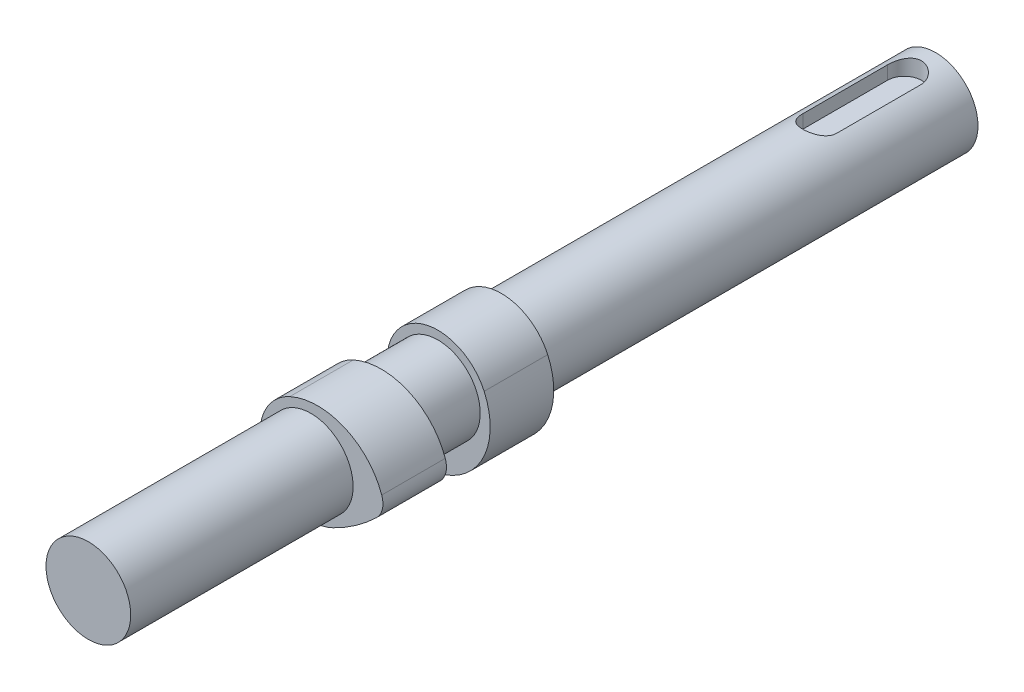
SolidWorks part; units mm, degrees
ref_plane "Front Plane" through (0, 0, 0) normal (0, 0, 1) x (1, 0, 0)
ref_plane "Top Plane" through (0, 0, 0) normal (0, 1, 0) x (1, 0, 0)
ref_plane "Right Plane" through (0, 0, 0) normal (1, 0, 0) x (0, 0, -1)
sketch "Sketch1" plane through (0, 0, 0) normal (0, 0, 1) x (1, 0, 0)
  circle A0 centre (0, 0) radius 10
  dimension "D1" = 20
extrude "Boss-Extrude1" add sketch "Sketch1" along normal blind 200
ref_plane "Plane1" through (0, 6, 0) normal (0, 1, 0) x (1, 0, 0)
sketch "Sketch2" plane through (0, 6, 0) normal (0, 1, 0) x (1, 0, 0)
  line L0 (0, -7.3661) -> (0, -27.3661) construction
  line L1 (4, -7.3661) -> (4, -27.3661)
  line L2 (-4, -7.3661) -> (-4, -27.3661)
  arc A0 (4, -7.3661) -> (-4, -7.3661) centre (0, -7.3661) ccw
  arc A1 (-4, -27.3661) -> (4, -27.3661) centre (0, -27.3661) ccw
  point P3 (0, -17.3661)
  point P8 (0, -3.3661)
  point P9 (0, -31.3661)
  point P10 (0, -7.3661)
  dimension "D3" = 4
  dimension "D1" = 28
  dimension "D2" = 20
extrude "Cut-Extrude1" cut sketch "Sketch2" along normal through all
ref_plane "Plane2" through (0, 0, 140) normal (0, 0, 1) x (1, 0, 0)
sketch "Sketch3" plane through (0, 0, 140) normal (0, 0, 1) x (1, 0, 0)
  arc A0 (-4.9527, 10.9303) -> (5.2775, -10.7772) centre (0, 0) ccw
  arc A1 (-4.9527, 10.9303) -> (16.7478, 1.6561) centre (1.6509, -3.6434) cw
  arc A2 (16.7478, 1.6561) -> (15.5077, -3.5924) centre (12.03, 0) cw
  arc A3 (15.5077, -3.5924) -> (5.2775, -10.7772) centre (-12.3142, 25.1468) cw
  point P1 (-5.9599, 10.4154)
  point P10 (23.7018, 1.0303)
  point P11 (23.7018, -4.5873)
  point P12 (24.4204, -2.8236)
  point P13 (1.2587, -11.9338)
  point P14 (23.7593, -4.3913)
  point P15 (5.613, -10.6063)
  dimension "D1" = 24
  dimension "D2" = 5
  dimension "D4" = 16
  dimension "D5" = 40
  dimension "D3" = 12.03
extrude "Boss-Extrude2" add sketch "Sketch3" along normal mid plane 15
ref_plane "Plane3" through (0, 0, 110) normal (0, 0, 1) x (1, 0, 0)
sketch "Sketch4" plane through (0, 0, 110) normal (0, 0, 1) x (1, 0, 0)
  line L0 (0, 20.4512) -> (0, -18.7588) construction
  arc A0 (10.9303, 4.9527) -> (-10.7772, -5.2775) centre (0, 0) ccw
  arc A1 (10.9303, 4.9527) -> (1.6561, -16.7478) centre (-3.6434, -1.6509) cw
  arc A2 (1.6561, -16.7478) -> (-3.5924, -15.5077) centre (0, -12.03) cw
  arc A3 (-3.5924, -15.5077) -> (-10.7772, -5.2775) centre (25.1468, 12.3142) cw
  point P9 (0, 0)
  point P12 (0, 0)
  point P13 (0, 0)
  point P14 (0, 0)
  point P15 (0, 0)
  point P16 (-36.402, 2.539)
  point P17 (0, 0)
  point P18 (-40.3917, 4.2154)
  dimension "D1" = 12
  dimension "D2" = 12.03
  dimension "D4" = 16
  dimension "D5" = 5
  dimension "D3" = 40
extrude "Boss-Extrude3" add sketch "Sketch4" along normal mid plane 15
